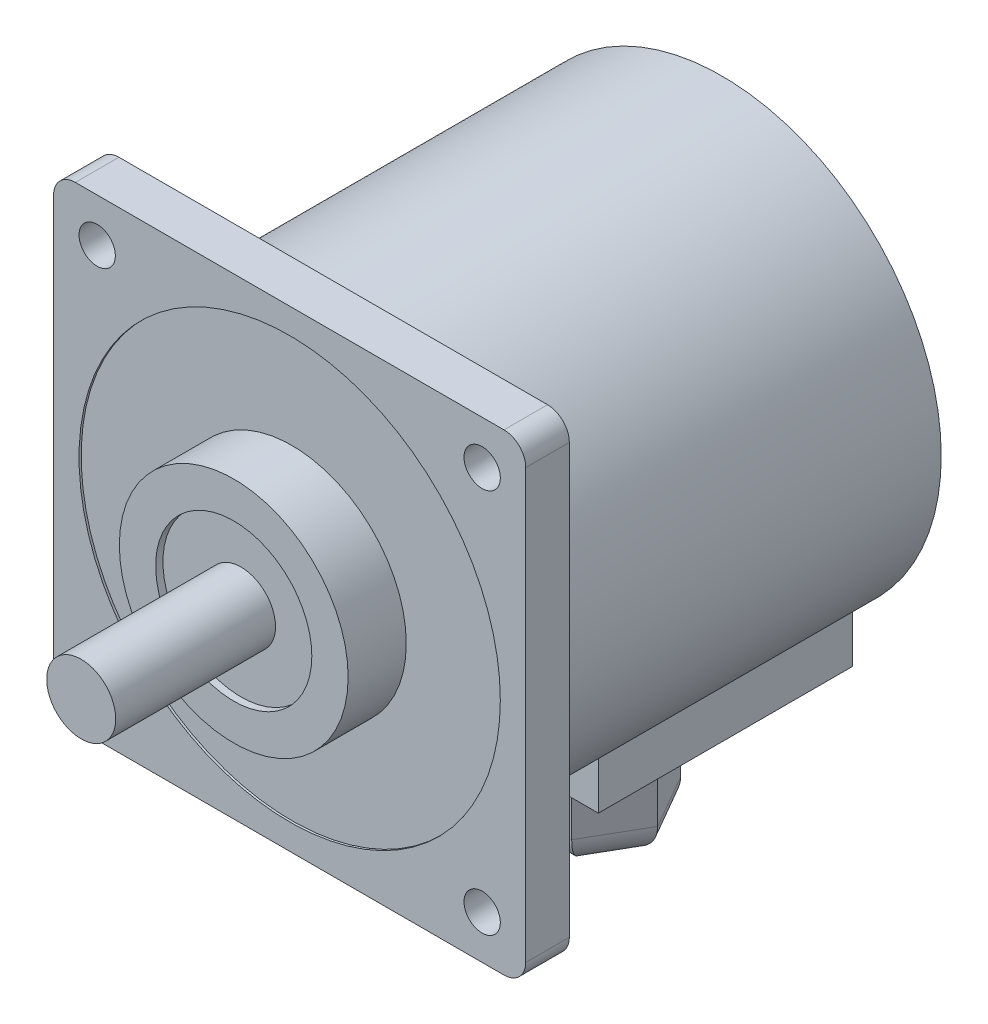
SolidWorks part; units mm, degrees
ref_plane "Ön Düzlem" through (0, 0, 0) normal (0, 0, 1) x (1, 0, 0)
ref_plane "Üst Düzlem" through (0, 0, 0) normal (0, 1, 0) x (1, 0, 0)
ref_plane "Sağ Düzlem" through (0, 0, 0) normal (1, 0, 0) x (0, 0, -1)
sketch "Çizim1" plane through (0, 0, 0) normal (0, 0, 1) x (1, 0, 0)
  line L1 (32.5, 32.5) -> (-32.5, 32.5)
  line L2 (32.5, 32.5) -> (32.5, -32.5)
  line L3 (32.5, -32.5) -> (-32.5, -32.5)
  line L4 (-32.5, 32.5) -> (-32.5, -32.5)
  line L5 (32.5, 32.5) -> (-32.5, -32.5) construction
  line L6 (32.5, -32.5) -> (-32.5, 32.5) construction
  point P0 (0, 0)
extrude "Yükseklik-Ekstrüzyon1" add sketch "Çizim1" along normal blind 6
sketch "Çizim2" plane through (0, 0, 0) normal (0, 0, -1) x (-1, 0, 0)
  circle A0 centre (0, 0) radius 30.2
extrude "Yükseklik-Ekstrüzyon2" add sketch "Çizim2" along normal blind 53.5
sketch "Çizim3" plane through (0, 0, -53.5) normal (0, 0, -1) x (-1, 0, 0)
  line L0 (0, -32.5) -> (-18, -32.5) construction
  line L1 (32.5, -32.5) -> (-32.5, -32.5) construction
  line L2 (-18, -32.5) -> (18, -32.5) construction
  line L3 (0, -30.2) -> (0, -31.2) construction
  line L4 (0, -31.2) -> (-18, -31.2) construction
  line L5 (-18, -31.2) -> (18, -31.2) construction
  line L6 (18, -31.2) -> (18, -24.2495)
  line L7 (-18, -31.2) -> (-18, -24.2495)
  line L8 (-18, -24.2495) -> (18, -24.2495)
  line L9 (-18, -31.2) -> (18, -31.2)
  circle A0 centre (0, 0) radius 30.2 construction
  circle A1 centre (0, 0) radius 30.2 construction
extrude "Yükseklik-Ekstrüzyon3" add sketch "Çizim3" against normal blind 35
sketch "Çizim5" plane through (0, 0, -53.5) normal (0, 0, -1) x (-1, 0, 0)
  line L0 (0, -25.2) -> (-25.2, 0) construction
  line L1 (-17.8191, -17.8191) -> (0, 0) construction
  line L2 (0, 0) -> (17.8191, -17.8191) construction
  circle A6 centre (0, 25.2) radius 1.5
  circle A7 centre (-17.8191, -17.8191) radius 1.5
  circle A8 centre (17.8191, -17.8191) radius 1.5
extrude "Kes-Ekstrüzyon2" cut sketch "Çizim5" against normal blind 10
sketch "Çizim30" plane through (0, 0, -53.5) normal (0, 0, -1) x (-1, 0, 0)
  line L0 (-17.8191, -17.8191) -> (-16.3191, -17.8191) construction
  line L1 (17.8191, -17.8191) -> (16.3191, -17.8191) construction
  line L2 (0, 25.2) -> (0, 23.7) construction
  circle A0 centre (-17.8191, -17.8191) radius 1.5 construction
  circle A1 centre (17.8191, -17.8191) radius 1.5 construction
  circle A2 centre (0, 25.2) radius 1.5 construction
sketch "Çizim31" plane through (0, 0, -43.5) normal (0, 0, -1) x (-1, 0, 0)
  circle A0 centre (0, 25.2) radius 1.5
  circle A1 centre (17.8191, -17.8191) radius 1.5
  circle A2 centre (-17.8191, -17.8191) radius 1.5
extrude "Yükseklik-Ekstrüzyon7" add sketch "Çizim31" along normal blind 10
hole_wizard "M3 SFHCS İçin Havşa5" positions "Çizim32" profile "Çizim33" countersink size "M3" standard "ANSI Metric"
sketch "Çizim32" plane through (0, 0, -53.5) normal (0, 0, -1) x (-1, 0, 0)
  point P0 (0, 25.2)
  point P3 (-17.8191, -17.8191)
  point P6 (17.8191, -17.8191)
sketch "Çizim33" plane through (0, 25.2, -53.5) normal (1, 0, 0) x (0, 1, 0)
  line L0 (0, 0) -> (0, 10.9614)
  line L1 (0, 10.9614) -> (1.6, 10)
  line L2 (1.6, 10) -> (1.6, 1.76)
  line L3 (1.6, 1.76) -> (3.36, 0)
  line L5 (3.36, 0) -> (0, 0)
  line L6 (-1.6, 1.76) -> (-3.36, 0) construction
  line L10 (0, 10.9614) -> (-1.6, 10) construction
  line L11 (0, -6.35) -> (0, 107.95) construction
  dimension "Hole Dia." = 3.2
  dimension "Hole Depth" = 10
  dimension "Near C'Sink Dia." = 6.72
  dimension "Near C'Sink Angle" = 90
  dimension "Drill Angle" = 118
sketch "Çizim34" plane through (0, -31.2, 0) normal (0, -1, 0) x (1, 0, 0)
  line L0 (-18, -36) -> (18, -36) construction
  line L1 (-18, -18.5) -> (-18, -53.5) construction
  line L2 (18, -18.5) -> (18, -53.5) construction
  line L4 (-8.6603, -36) -> (-4.3301, -43.5)
  line L5 (-4.3301, -43.5) -> (4.3301, -43.5)
  line L6 (4.3301, -43.5) -> (8.6603, -36)
  line L7 (8.6603, -36) -> (4.3301, -28.5)
  line L8 (4.3301, -28.5) -> (-4.3301, -28.5)
  line L9 (-4.3301, -28.5) -> (-8.6603, -36)
  circle A0 centre (0, -36) radius 7.5 construction
extrude "Yükseklik-Ekstrüzyon8" add sketch "Çizim34" along normal blind 19
fillet "Radyus1" radius 4 6 edges at (-6.4952, -50.2, -32.25) (0, -50.2, -28.5) (6.4952, -50.2, -32.25) (6.4952, -50.2, -39.75) (0, -50.2, -43.5) (-6.4952, -50.2, -39.75)
sketch "Çizim35" plane through (0, 0, 6) normal (0, 0, 1) x (1, 0, 0)
  circle A0 centre (0, 0) radius 29
extrude "Kes-Ekstrüzyon3" cut sketch "Çizim35" against normal blind 0.3
sketch "Çizim36" plane through (0, 0, 5.7) normal (0, 0, 1) x (1, 0, 0)
  circle A0 centre (0, 0) radius 15.75
extrude "Yükseklik-Ekstrüzyon9" add sketch "Çizim36" along normal blind 8
sketch "Çizim37" plane through (0, 0, 13.7) normal (0, 0, 1) x (1, 0, 0)
  circle A0 centre (0, 0) radius 10.75
extrude "Kes-Ekstrüzyon4" cut sketch "Çizim37" against normal blind 1
sketch "Çizim38" plane through (0, 0, 12.7) normal (0, 0, 1) x (1, 0, 0)
  circle A0 centre (0, 0) radius 4.75
extrude "Yükseklik-Ekstrüzyon10" add sketch "Çizim38" along normal blind 22
sketch "Çizim39" plane through (0, 0, 6) normal (0, 0, 1) x (1, 0, 0)
  line L0 (32.5, 32.5) -> (32.5, 26.5) construction
  line L1 (32.5, -32.5) -> (32.5, 32.5) construction
  line L2 (32.5, 26.5) -> (26.5, 26.5) construction
  line L3 (-32.5, 32.5) -> (-32.5, 26.5) construction
  line L4 (-32.5, 32.5) -> (-32.5, -32.5) construction
  line L5 (-32.5, 26.5) -> (-26.5, 26.5) construction
  line L6 (-26.5, 26.5) -> (-26.5, -32.5) construction
  line L7 (-32.5, -32.5) -> (32.5, -32.5) construction
  line L8 (-26.5, -32.5) -> (-26.5, -26.5) construction
  line L9 (-26.5, -26.5) -> (26.5, -26.5) construction
  circle A0 centre (26.5, -26.5) radius 2.5
  circle A1 centre (-26.5, -26.5) radius 2.5
  circle A2 centre (-26.5, 26.5) radius 2.5
  circle A3 centre (26.5, 26.5) radius 2.5
extrude "Kes-Ekstrüzyon5" cut sketch "Çizim39" against normal blind 10
fillet "Radyus2" radius 3 4 edges at (-32.5, -32.5, 3) (32.5, -32.5, 3) (32.5, 32.5, 3) (-32.5, 32.5, 3)
